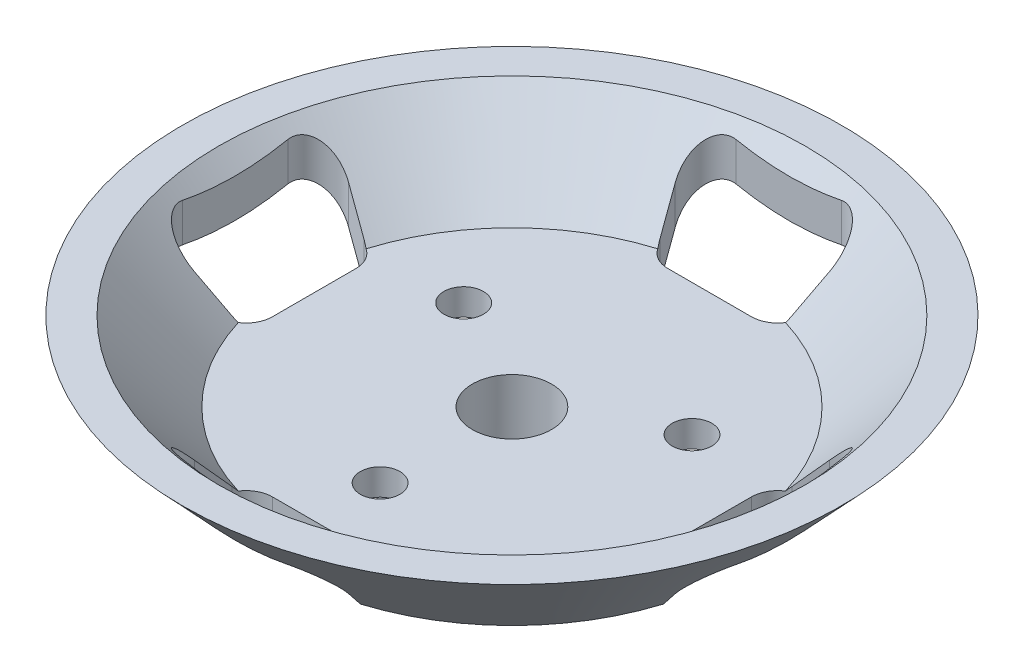
SolidWorks part; units mm, degrees
ref_plane "Front Plane" through (0, 0, 0) normal (0, 0, 1) x (1, 0, 0)
ref_plane "Top Plane" through (0, 0, 0) normal (0, 1, 0) x (1, 0, 0)
ref_plane "Right Plane" through (0, 0, 0) normal (1, 0, 0) x (0, 0, -1)
sketch "Sketch1" plane through (0, 0, 0) normal (0, 1, 0) x (1, 0, 0)
  circle A0 centre (0, 0) radius 17.5
  dimension "D1" = 35
ref_plane "Plane1" through (0, 8, 0) normal (0, 1, 0) x (1, 0, 0)
sketch "Sketch2" plane through (0, 8, 0) normal (0, 1, 0) x (1, 0, 0)
  circle A0 centre (0, 0) radius 25
  dimension "D1" = 50
loft "Loft1" add profiles "Sketch1", "Sketch2"
shell "Shell1" thickness 2
sketch "Sketch3" plane through (0, 0, 0) normal (0, -1, 0) x (1, 0, 0)
  circle A0 centre (0, 0) radius 7.25
  circle A1 centre (0, 0) radius 3
  dimension "D1" = 14.5
  dimension "D2" = 6
extrude "Boss-Extrude1" add sketch "Sketch3" along normal blind 5
sketch "Sketch4" plane through (0, 0, 0) normal (0, -1, 0) x (1, 0, 0)
  circle A1 centre (0, 0) radius 3
  circle A2 centre (0, 0) radius 3
  dimension "D1" = 0
extrude "Cut-Extrude1" cut sketch "Sketch4" against normal blind 5
sketch "Sketch5" plane through (0, 0, 0) normal (0, -1, 0) x (1, 0, 0)
  circle A0 centre (0, 0) radius 10 construction
  circle A1 centre (0, 10) radius 1.5
  circle A2 centre (8.6603, -5) radius 1.5
  circle A3 centre (-8.6603, -5) radius 1.5
  point P11 (0, 0)
  dimension "D1" = 20
  dimension "D2" = 3
  dimension "D4" = 17.3205
  dimension "D5" = 8.6603
  dimension "D3" = 3
extrude "Cut-Extrude2" cut sketch "Sketch5" against normal through all
sketch "Sketch6" plane through (0, -5, 0) normal (0, -1, 0) x (1, 0, 0)
  line L0 (-5.0128, 16.2308) -> (-5.8462, 18.2308)
  line L1 (-4, 21) -> (4, 21)
  line L2 (5.8462, 18.2308) -> (5.0128, 16.2308)
  line L3 (3.1667, 15) -> (-3.1667, 15)
  line L4 (15, -3.1667) -> (15, 3.1667)
  line L5 (16.2308, 5.0128) -> (18.2308, 5.8462)
  line L6 (21, 4) -> (21, -4)
  line L7 (18.2308, -5.8462) -> (16.2308, -5.0128)
  line L8 (-3.1667, -15) -> (3.1667, -15)
  line L9 (5.0128, -16.2308) -> (5.8462, -18.2308)
  line L10 (4, -21) -> (-4, -21)
  line L11 (-5.8462, -18.2308) -> (-5.0128, -16.2308)
  line L12 (-15, 3.1667) -> (-15, -3.1667)
  line L13 (-16.2308, -5.0128) -> (-18.2308, -5.8462)
  line L14 (-21, -4) -> (-21, 4)
  line L15 (-18.2308, 5.8462) -> (-16.2308, 5.0128)
  arc A0 (-3.1667, 15) -> (-5.0128, 16.2308) centre (-3.1667, 17) cw
  arc A1 (5.0128, 16.2308) -> (3.1667, 15) centre (3.1667, 17) cw
  arc A2 (5.8462, 18.2308) -> (4, 21) centre (4, 19) ccw
  arc A3 (-5.8462, 18.2308) -> (-4, 21) centre (-4, 19) cw
  arc A4 (16.2308, -5.0128) -> (15, -3.1667) centre (17, -3.1667) cw
  arc A5 (15, 3.1667) -> (16.2308, 5.0128) centre (17, 3.1667) cw
  arc A6 (18.2308, 5.8462) -> (21, 4) centre (19, 4) cw
  arc A7 (18.2308, -5.8462) -> (21, -4) centre (19, -4) ccw
  arc A8 (-5.0128, -16.2308) -> (-3.1667, -15) centre (-3.1667, -17) cw
  arc A9 (3.1667, -15) -> (5.0128, -16.2308) centre (3.1667, -17) cw
  arc A10 (5.8462, -18.2308) -> (4, -21) centre (4, -19) cw
  arc A11 (-5.8462, -18.2308) -> (-4, -21) centre (-4, -19) ccw
  arc A12 (-16.2308, 5.0128) -> (-15, 3.1667) centre (-17, 3.1667) cw
  arc A13 (-15, -3.1667) -> (-16.2308, -5.0128) centre (-17, -3.1667) cw
  arc A14 (-18.2308, -5.8462) -> (-21, -4) centre (-19, -4) cw
  arc A15 (-18.2308, 5.8462) -> (-21, 4) centre (-19, 4) ccw
  point P4 (0, 15)
  point P5 (0, 21)
  point P9 (-4.5, 15)
  point P12 (4.5, 15)
  point P17 (-7, 21)
  point P57 (0, 0)
  dimension "D5" = 2
  dimension "D1" = 15
  dimension "D2" = 9
  dimension "D3" = 6
  dimension "D4" = 7
  dimension "D7" = 15
  dimension "D8" = 3.1667
  dimension "D6" = 4
extrude "Cut-Extrude3" cut sketch "Sketch6" against normal blind 15
